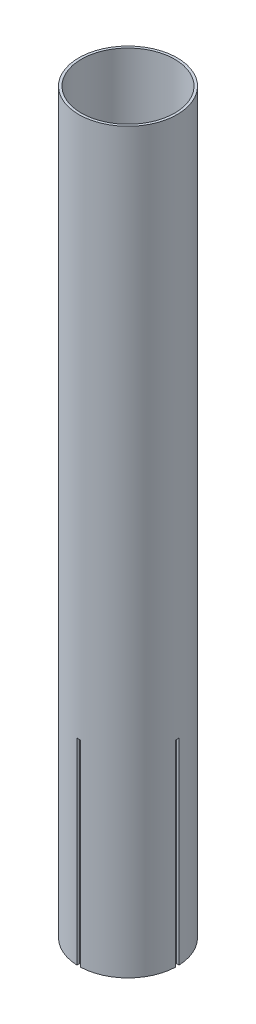
SolidWorks part; units mm, degrees
ref_plane "Front Plane" through (0, 0, 0) normal (0, 0, 1) x (1, 0, 0)
ref_plane "Top Plane" through (0, 0, 0) normal (0, 1, 0) x (1, 0, 0)
ref_plane "Right Plane" through (0, 0, 0) normal (1, 0, 0) x (0, 0, -1)
sketch "Sketch1" plane through (0, 0, 0) normal (0, 1, 0) x (1, 0, 0)
  circle A0 centre (0, 0) radius 38
  circle A1 centre (0, 0) radius 40
  dimension "D1" = 80
  dimension "D2" = 2
extrude "Boss-Extrude1" add sketch "Sketch1" along normal blind 600
sketch "Sketch2" plane through (0, 0, 0) normal (1, 0, 0) x (0, 0, -1)
  line L0 (-40, 0) -> (40, 0) construction
  line L1 (1.5, 160) -> (-1.5, 160)
  line L2 (1.5, 160) -> (1.5, 0)
  line L3 (1.5, 0) -> (-1.5, 0)
  line L4 (-1.5, 160) -> (-1.5, 0)
  line L5 (1.5, 160) -> (-1.5, 0) construction
  line L6 (1.5, 0) -> (-1.5, 160) construction
  point P0 (0, 80)
  dimension "D1" = 3
  dimension "D2" = 160
extrude "Cut-Extrude1" cut sketch "Sketch2" against normal through all
pattern_circular "CirPattern1" count 4 over 360 about axis through (0, 0, 0) along (0, 1, 0) of "Cut-Extrude1"
